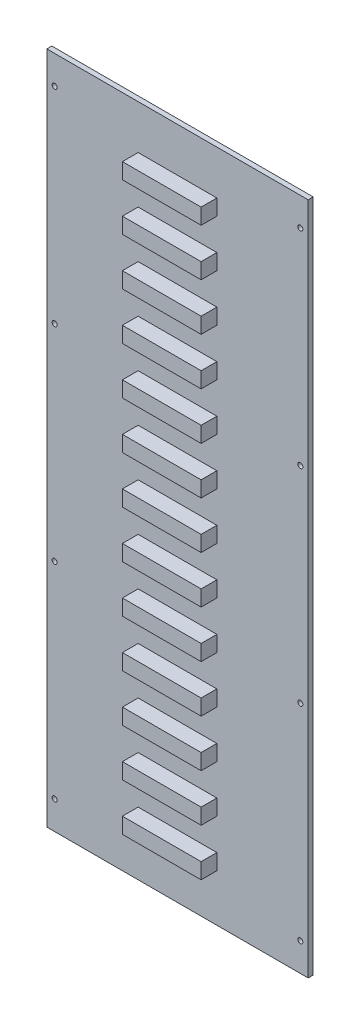
SolidWorks part; units mm, degrees
ref_plane "Front Plane" through (0, 0, 0) normal (0, 0, 1) x (1, 0, 0)
ref_plane "Top Plane" through (0, 0, 0) normal (0, 1, 0) x (1, 0, 0)
ref_plane "Right Plane" through (0, 0, 0) normal (1, 0, 0) x (0, 0, -1)
sketch "Sketch1" plane through (0, 0, 0) normal (0, 0, 1) x (1, 0, 0)
  line L1 (-41.5, -107) -> (41.5, -107)
  line L2 (-41.5, -107) -> (-41.5, 107)
  line L3 (-41.5, 107) -> (41.5, 107)
  line L4 (41.5, -107) -> (41.5, 107)
  line L5 (-41.5, -107) -> (41.5, 107) construction
  line L6 (-41.5, 107) -> (41.5, -107) construction
  point P0 (0, 0)
  dimension "D1" = 83
  dimension "D2" = 214
extrude "Boss-Extrude1" add sketch "Sketch1" along normal blind 1.5875
sketch "Sketch2" plane through (0, 0, 1.5875) normal (0, 0, 1) x (1, 0, 0)
  line L0 (0, -107) -> (0, 107) construction
  line L1 (-12.5, 88) -> (12.5, 88)
  line L2 (-12.5, 88) -> (-12.5, 93)
  line L3 (-12.5, 93) -> (12.5, 93)
  line L4 (12.5, 88) -> (12.5, 93)
  line L5 (-12.5, 88) -> (12.5, 93) construction
  line L6 (-12.5, 93) -> (12.5, 88) construction
  line L7 (41.5, 107) -> (-41.5, 107) construction
  line L8 (-12.5, 73) -> (12.5, 73)
  line L9 (-12.5, 73) -> (-12.5, 78)
  line L10 (-12.5, 78) -> (12.5, 78)
  line L11 (12.5, 73) -> (12.5, 78)
  line L12 (-12.5, 73) -> (12.5, 78) construction
  line L13 (-12.5, 78) -> (12.5, 73) construction
  line L14 (-12.5, 58) -> (12.5, 58)
  line L15 (-12.5, 58) -> (-12.5, 63)
  line L16 (-12.5, 63) -> (12.5, 63)
  line L17 (12.5, 58) -> (12.5, 63)
  line L18 (-12.5, 58) -> (12.5, 63) construction
  line L19 (-12.5, 63) -> (12.5, 58) construction
  line L20 (-12.5, 43) -> (12.5, 43)
  line L21 (-12.5, 43) -> (-12.5, 48)
  line L22 (-12.5, 48) -> (12.5, 48)
  line L23 (12.5, 43) -> (12.5, 48)
  line L24 (-12.5, 43) -> (12.5, 48) construction
  line L25 (-12.5, 48) -> (12.5, 43) construction
  line L26 (-12.5, 28) -> (12.5, 28)
  line L27 (-12.5, 28) -> (-12.5, 33)
  line L28 (-12.5, 33) -> (12.5, 33)
  line L29 (12.5, 28) -> (12.5, 33)
  line L30 (-12.5, 28) -> (12.5, 33) construction
  line L31 (-12.5, 33) -> (12.5, 28) construction
  line L32 (-12.5, 13) -> (12.5, 13)
  line L33 (-12.5, 13) -> (-12.5, 18)
  line L34 (-12.5, 18) -> (12.5, 18)
  line L35 (12.5, 13) -> (12.5, 18)
  line L36 (-12.5, 13) -> (12.5, 18) construction
  line L37 (-12.5, 18) -> (12.5, 13) construction
  line L38 (-12.5, -2) -> (12.5, -2)
  line L39 (-12.5, -2) -> (-12.5, 3)
  line L40 (-12.5, 3) -> (12.5, 3)
  line L41 (12.5, -2) -> (12.5, 3)
  line L42 (-12.5, -2) -> (12.5, 3) construction
  line L43 (-12.5, 3) -> (12.5, -2) construction
  line L44 (-12.5, -17) -> (12.5, -17)
  line L45 (-12.5, -17) -> (-12.5, -12)
  line L46 (-12.5, -12) -> (12.5, -12)
  line L47 (12.5, -17) -> (12.5, -12)
  line L48 (-12.5, -17) -> (12.5, -12) construction
  line L49 (-12.5, -12) -> (12.5, -17) construction
  line L50 (-12.5, -32) -> (12.5, -32)
  line L51 (-12.5, -32) -> (-12.5, -27)
  line L52 (-12.5, -27) -> (12.5, -27)
  line L53 (12.5, -32) -> (12.5, -27)
  line L54 (-12.5, -32) -> (12.5, -27) construction
  line L55 (-12.5, -27) -> (12.5, -32) construction
  line L56 (-12.5, -47) -> (12.5, -47)
  line L57 (-12.5, -47) -> (-12.5, -42)
  line L58 (-12.5, -42) -> (12.5, -42)
  line L59 (12.5, -47) -> (12.5, -42)
  line L60 (-12.5, -47) -> (12.5, -42) construction
  line L61 (-12.5, -42) -> (12.5, -47) construction
  line L62 (-12.5, -62) -> (12.5, -62)
  line L63 (-12.5, -62) -> (-12.5, -57)
  line L64 (-12.5, -57) -> (12.5, -57)
  line L65 (12.5, -62) -> (12.5, -57)
  line L66 (-12.5, -62) -> (12.5, -57) construction
  line L67 (-12.5, -57) -> (12.5, -62) construction
  line L68 (-12.5, -77) -> (12.5, -77)
  line L69 (-12.5, -77) -> (-12.5, -72)
  line L70 (-12.5, -72) -> (12.5, -72)
  line L71 (12.5, -77) -> (12.5, -72)
  line L72 (-12.5, -77) -> (12.5, -72) construction
  line L73 (-12.5, -72) -> (12.5, -77) construction
  line L74 (-12.5, -92) -> (12.5, -92)
  line L75 (-12.5, -92) -> (-12.5, -87)
  line L76 (-12.5, -87) -> (12.5, -87)
  line L77 (12.5, -92) -> (12.5, -87)
  line L78 (-12.5, -92) -> (12.5, -87) construction
  line L79 (-12.5, -87) -> (12.5, -92) construction
  point P0 (0, 90.5)
  point P5 (0, -29.5)
  point P11 (0, 0)
  point P13 (0, 75.5)
  point P18 (0, 60.5)
  point P23 (0, 45.5)
  point P28 (0, 30.5)
  point P33 (0, 15.5)
  point P38 (0, 0.5)
  point P43 (0, -14.5)
  point P51 (0, -44.5)
  point P56 (0, -59.5)
  point P61 (0, -74.5)
  point P66 (0, -89.5)
  dimension "D1" = 25
  dimension "D2" = 5
  dimension "D3" = 19
  dimension "D5" = 15
  dimension "D4" = 13
extrude "Boss-Extrude2" add sketch "Sketch2" along normal blind 5
hole_wizard "#0 Clearance Hole1" positions "Sketch5" profile "Sketch3" hole size "#0" standard "ANSI Inch"
sketch "Sketch5" plane through (0, 0, 1.5875) normal (0, 0, 1) x (1, 0, 0)
  line L0 (0, 0) -> (0, 107) construction
  line L1 (41.5, 107) -> (-41.5, 107) construction
  line L4 (-41.5, 107) -> (-41.5, -107) construction
  line L5 (-41.5, 0) -> (41.5, 0) construction
  line L6 (41.5, -107) -> (41.5, 107) construction
  point P490 (-39, 98)
  point P492 (39, 98)
  point P533 (-39, 32.6667)
  point P534 (39, 32.6667)
  point P535 (-39, -32.6667)
  point P536 (39, -32.6667)
  point P537 (-39, -98)
  point P538 (39, -98)
  dimension "D1" = 2.5
  dimension "D2" = 4
  dimension "D3" = 196
sketch "Sketch3" plane through (-39, 98, 1.5875) normal (1, 0, 0) x (0, -1, 0)
  line L0 (0, 0) -> (0, 3.6596)
  line L1 (0, 3.6596) -> (0.8064, 3.175)
  line L2 (0.8064, 3.175) -> (0.8064, 0)
  line L5 (0.8064, 0) -> (0, 0)
  line L10 (0, 3.6596) -> (-0.8065, 3.175) construction
  line L11 (0, -6.35) -> (0, 107.95) construction
  dimension "Hole Dia." = 1.6129
  dimension "Hole Depth" = 3.175
  dimension "Drill Angle" = 118
sketch "Sketch6" plane through (0, 0, 0) normal (0, 0, -1) x (-1, 0, 0)
  line L0 (41.5, -7) -> (-41.5, -7) construction
  line L1 (-36.2, 0) -> (36.3, 0)
  line L2 (-36.2, 0) -> (-36.2, -7)
  line L3 (-36.2, -7) -> (36.3, -7)
  line L4 (36.3, 0) -> (36.3, -7)
  dimension "D1" = 72.5
extrude "Boss-Extrude3" add sketch "Sketch6" along normal blind 4.9125
